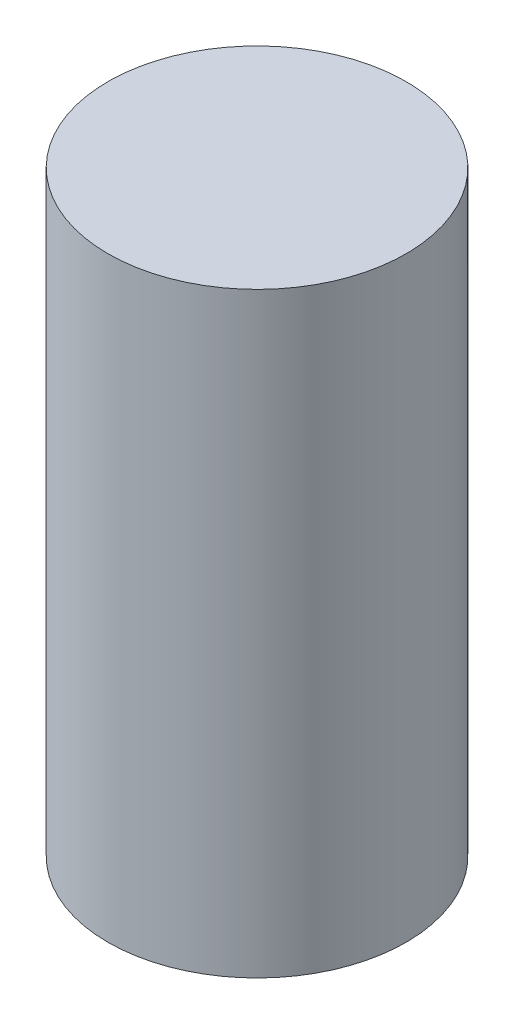
SolidWorks part; units mm, degrees
ref_plane "前视基准面" through (0, 0, 0) normal (0, 0, 1) x (1, 0, 0)
ref_plane "上视基准面" through (0, 0, 0) normal (0, 1, 0) x (1, 0, 0)
ref_plane "右视基准面" through (0, 0, 0) normal (1, 0, 0) x (0, 0, -1)
other "Configuration Table"
sketch "草图2" plane through (0, 0, 0) normal (0, 1, 0) x (1, 0, 0)
  circle A0 centre (0, 0) radius 10
  dimension "D1" = 20
extrude "凸台-拉伸1" add sketch "草图2" along normal blind 40 contours A0
sketch "草图3" plane through (0, 0, 0) normal (1, 0, 0) x (0, 0, -1)
  line L0 (10, 40) -> (-10, 40) construction
  line L1 (-10, 40) -> (-10, 0) construction
  circle A0 centre (0, 20) radius 2.5
  dimension "D1" = 20
  dimension "D2" = 10
extrude "切除-拉伸1" cut sketch "草图3" against normal blind 40
